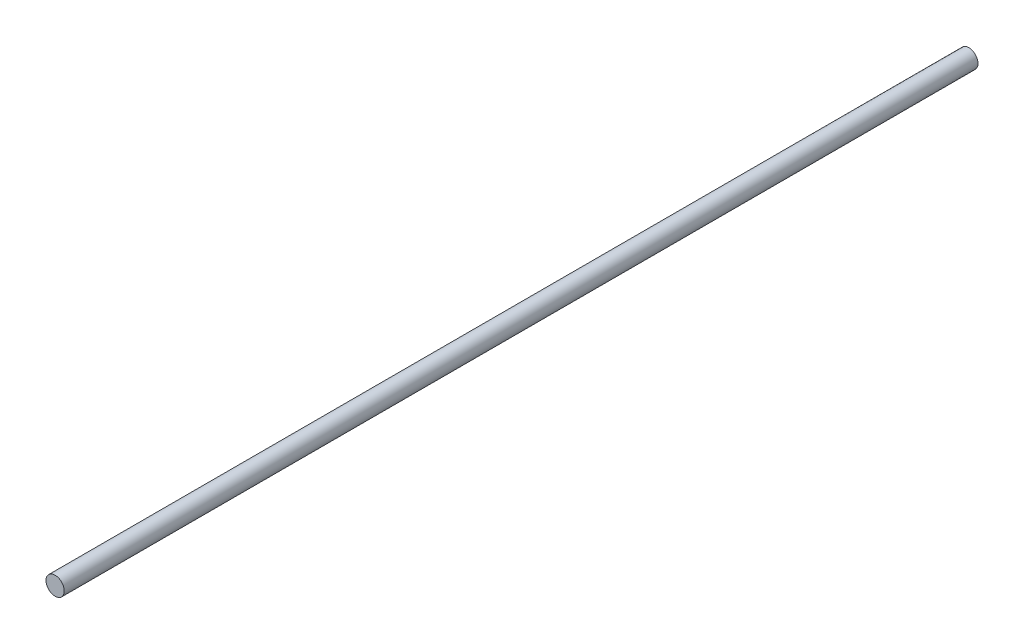
SolidWorks part; units mm, degrees
ref_plane "Plano frontal" through (0, 0, 0) normal (0, 0, 1) x (1, 0, 0)
ref_plane "Plano superior" through (0, 0, 0) normal (0, 1, 0) x (1, 0, 0)
ref_plane "Plano direito" through (0, 0, 0) normal (1, 0, 0) x (0, 0, -1)
sketch "Esboço1" plane through (0, 0, 0) normal (0, 0, 1) x (1, 0, 0)
  circle A0 centre (0, 0) radius 4
  dimension "D1" = 8
extrude "Ressalto-extrusão1" add sketch "Esboço1" along normal blind 400
